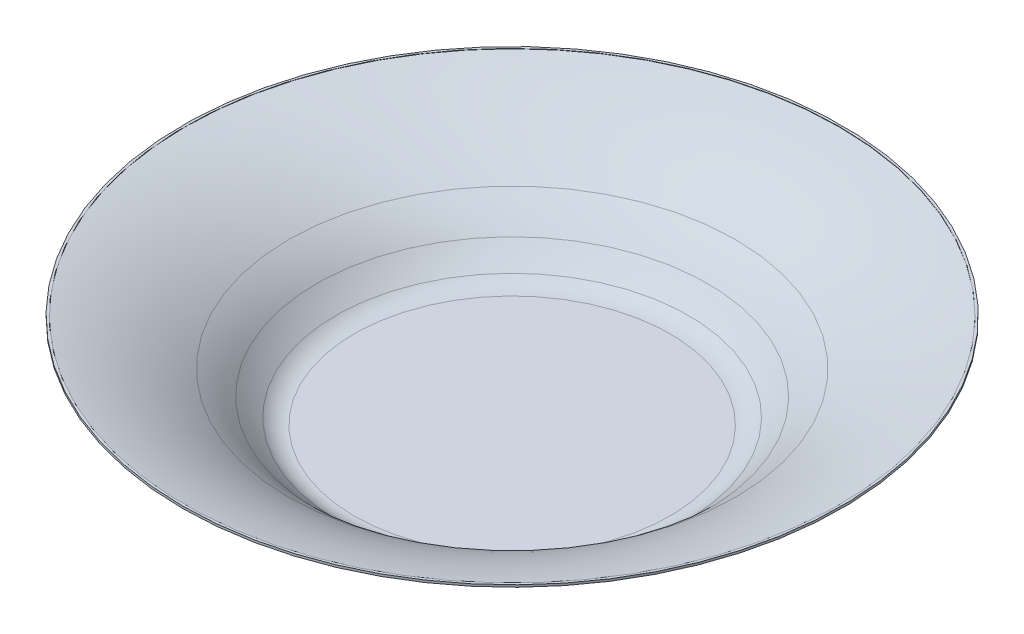
SolidWorks part; units mm, degrees
ref_plane "Front Plane" through (0, 0, 0) normal (0, 0, 1) x (1, 0, 0)
ref_plane "Top Plane" through (0, 0, 0) normal (0, 1, 0) x (1, 0, 0)
ref_plane "Right Plane" through (0, 0, 0) normal (1, 0, 0) x (0, 0, -1)
sketch "Sketch1" plane through (0, 0, 0) normal (0, 0, 1) x (1, 0, 0)
  line L2 (0, 0) -> (70.1703, 0)
  line L5 (146.4749, 42.0676) -> (146.4749, 43.0436)
  line L8 (0, 0) -> (0, -110.023) construction
  line L9 (0, 0) -> (0, 101.5708) construction
  line L10 (146.4749, 43.0436) -> (0, 43.0436)
  line L11 (0, 43.0436) -> (0, 0)
  arc A0 (70.1703, 0) -> (79.0163, 3.1599) centre (70.1703, 13.9619) ccw
  arc A1 (79.0163, 3.1599) -> (87.6388, 11.2753) centre (24.553, 69.6656) ccw
  arc A2 (87.6388, 11.2753) -> (99.8118, 21.9266) centre (144.1614, -41.0403) cw
  arc A3 (99.8118, 21.9266) -> (146.4749, 42.0676) centre (171.2981, -79.5685) cw
revolve "Revolve3" add sketch "Sketch1" angle 360 about L11
shell "Shell2" thickness 1
